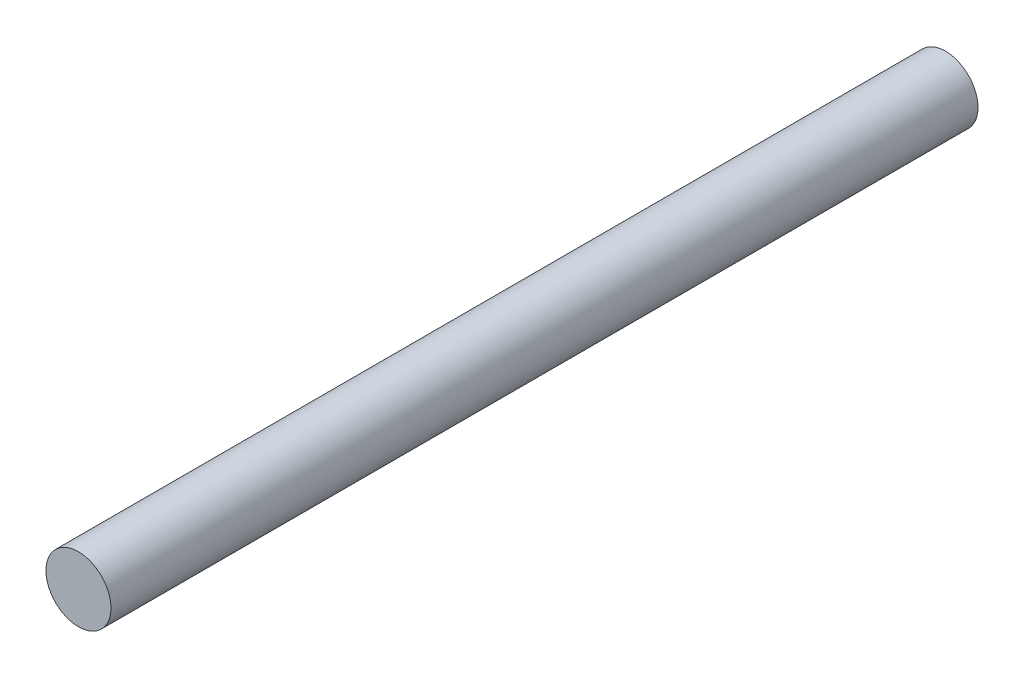
SolidWorks part; units mm, degrees
ref_plane "Plan de face" through (0, 0, 0) normal (0, 0, 1) x (1, 0, 0)
ref_plane "Plan de dessus" through (0, 0, 0) normal (0, 1, 0) x (1, 0, 0)
ref_plane "Plan de droite" through (0, 0, 0) normal (1, 0, 0) x (0, 0, -1)
sketch "Esquisse1" plane through (0, 0, 0) normal (0, 0, 1) x (1, 0, 0)
  circle A0 centre (0, 0) radius 7.5
  dimension "D1" = 15
extrude "Boss.-Extru.1" add sketch "Esquisse1" along normal blind 200
